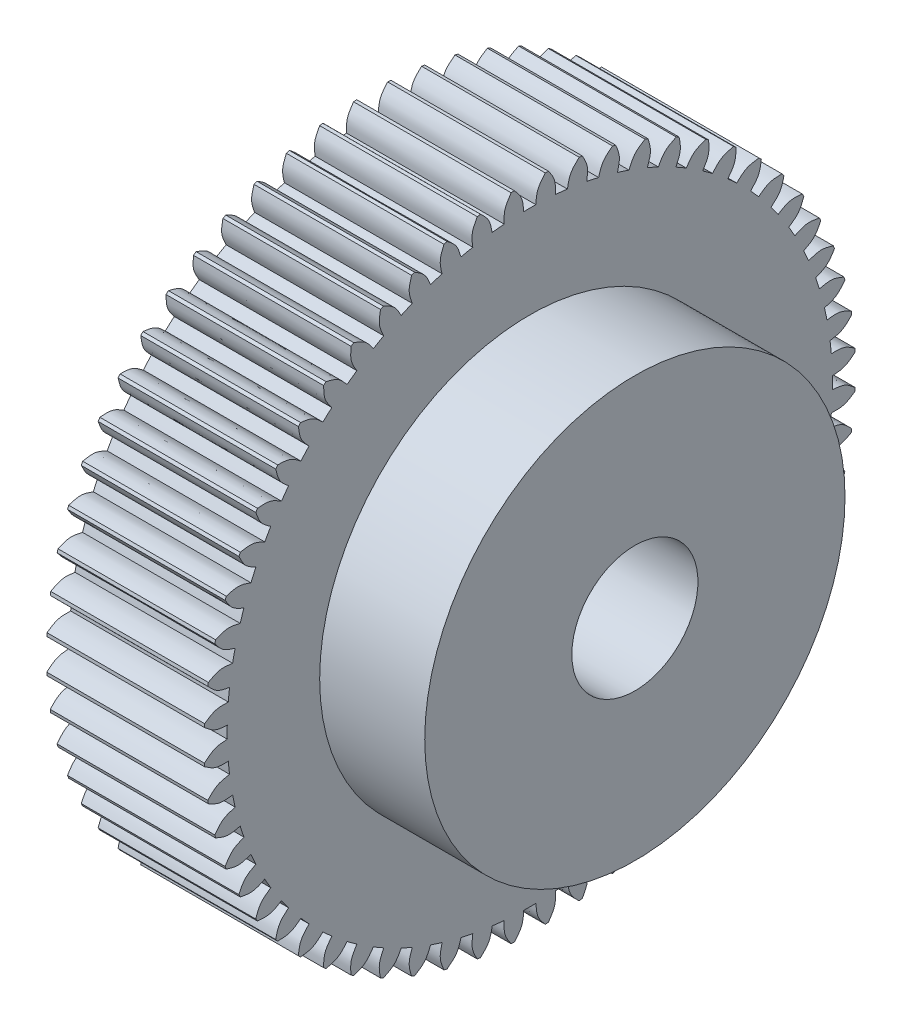
SolidWorks part; units mm, degrees
ref_plane "Front" through (0, 0, 0) normal (0, 0, 1) x (1, 0, 0)
ref_plane "Top" through (0, 0, 0) normal (0, 1, 0) x (1, 0, 0)
ref_plane "Right" through (0, 0, 0) normal (1, 0, 0) x (0, 0, -1)
sketch "Ritning 1" plane through (0, 0, 0) normal (0, 0, 1) x (1, 0, 0)
  line L0 (-12.5, -15.5) -> (12.5, -15.5) construction
  line L1 (-12.5, -9.5) -> (12.5, -9.5)
  line L2 (12.5, -9.5) -> (12.5, 4.5)
  line L3 (12.5, 4.5) -> (2.5, 4.5)
  line L4 (2.5, 4.5) -> (2.5, 15.5)
  line L5 (2.5, 15.5) -> (-12.5, 15.5)
  line L6 (-12.5, 15.5) -> (-12.5, -9.5)
  line L7 (-12.5, -9.5) -> (-12.5, -15.5) construction
  line L8 (12.5, -15.5) -> (12.5, -9.5) construction
  line L9 (-12.5, -15.5) -> (12.5, -15.5) construction
  dimension "D1" = 2.5
  dimension "D2" = 12.5
  dimension "D3" = 12.5
  dimension "D4" = 4.5
  dimension "D5" = 15.5
  dimension "D6" = 15.5
revolve "Kugghjulsämne" add sketch "Ritning 1" angle 360 about L0
sketch "Ritning 2" plane through (-12.5, 0, 0) normal (-1, 0, 0) x (0, 0, 1)
  line L0 (0, -15.5) -> (0, 15.5) construction
  line L1 (1.4684, 15.4652) -> (0, 16.9336)
  line L2 (-1.4684, 15.4652) -> (0, 16.9336)
  line L3 (0, -15.5) -> (4.1805, -15.5) construction
  arc A0 (0.5746, 13.2943) -> (-0.5746, 13.2943) centre (0, -15.5) ccw
  circle A1 centre (0, -15.5) radius 31 construction
  spline S0 degree 3 poles (1.4684, 15.4652) (1.2015, 15.1563) (0.6623, 14.5326) (0.604, 13.7097) (0.5746, 13.2943) knots 0 0 0 0 0.495208 1 1 1 1
  spline S1 degree 3 poles (-1.4684, 15.4652) (-1.2015, 15.1563) (-0.6623, 14.5326) (-0.604, 13.7097) (-0.5746, 13.2943) knots 0 0 0 0 0.495208 1 1 1 1
  dimension "D1" = 28.8
  dimension "D2" = 0.5746
  dimension "D3" = 0.7854
  dimension "D4" = 1.4684
  dimension "D5" = 29.9897
  dimension "D6" = 0.7854
  dimension "D7" = 30.9652
extrude "Kugglucka" cut sketch "Ritning 2" against normal up to surface (15 mm away) up to face at (2.5, -15.5, 31)
pattern_circular "CirPattern" count 60 over 360 about axis through (-12.5, -15.5, 0) along (-1, 0, 0) of "Kugglucka"
